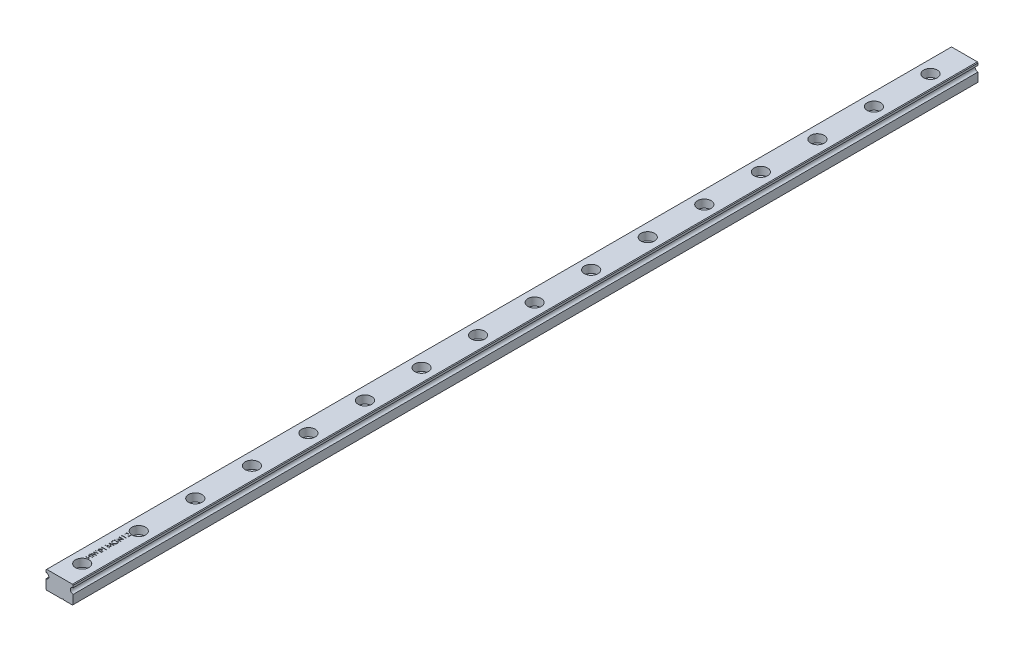
SolidWorks part; units mm, degrees
material "镀铬不锈钢"
ref_plane "前视基准面" through (0, 0, 0) normal (0, 0, 1) x (1, 0, 0)
ref_plane "上视基准面" through (0, 0, 0) normal (0, 1, 0) x (1, 0, 0)
ref_plane "右视基准面" through (0, 0, 0) normal (1, 0, 0) x (0, 0, -1)
sketch "草图1" plane through (0, 0, 0) normal (0, 0, 1) x (1, 0, 0)
  line L2 (-5.7, 0) -> (1.2, 0)
  line L3 (6, 0.3) -> (6, 4.25)
  line L4 (5.7, 0) -> (6, 0.3)
  line L5 (5.7, 8) -> (-5.7, 8)
  line L6 (-6, 0.3) -> (-5.7, 0)
  line L7 (6, 7.7) -> (5.7, 8)
  line L8 (-6, 7.7) -> (-6, 6.75)
  line L9 (-6, 4.25) -> (-6, 0.3)
  line L10 (0, 8) -> (0, 0) construction
  line L11 (-5.7, 8) -> (-6, 7.7)
  line L12 (1.8, 0) -> (5.7, 0)
  line L13 (6, 6.75) -> (6, 7.7)
  arc A0 (-6, 4.25) -> (-6, 6.75) centre (-6, 5.5) ccw
  arc A1 (1.8, 0) -> (1.2, 0) centre (1.5, 0) ccw
  arc A2 (6, 6.75) -> (6, 4.25) centre (6, 5.5) ccw
extrude "凸台-拉伸1" add sketch "草图1" against normal blind 400
hole_wizard "M3 六角凹头螺钉的柱形沉头孔1" positions "草图3" profile "草图2" counterbore size "M3" standard "ISO" end condition through all
sketch "草图3" plane through (1.75, 8, 16.5167) normal (0, 1, 0) x (-1, 0, 0)
  point P0 (1.75, -26.5167)
  dimension "D1" = 10
sketch "草图2" plane through (0, 8, -10) normal (1, 0, 0) x (0, 0, 1)
  line L0 (0, 0) -> (0, 8)
  line L1 (0, 8) -> (1.75, 8)
  line L3 (1.75, 8) -> (1.75, 3.5)
  line L4 (1.75, 3.5) -> (3, 3.5)
  line L5 (3, 3.5) -> (3, 0)
  line L7 (3, 0) -> (0, 0)
  line L11 (0, -6.35) -> (0, 107.95) construction
  dimension "通孔孔直径" = 3.5
  dimension "通孔孔深度" = 8
  dimension "柱形沉头孔直径" = 6
  dimension "柱形沉头孔深度" = 3.5
pattern_linear "阵列(线性)1" count 16 spacing 25 along (0, 0, -1) of "M3 六角凹头螺钉的柱形沉头孔1"
sketch "草图6" plane through (0, 8, 0) normal (0, 1, 0) x (1, 0, 0)
  line L0 (0, 10) -> (0, 35) construction
  text T0 "HIWIN MGN12" font "Century Gothic" height 2
extrude "切除-拉伸1" cut sketch "草图6" against normal blind 0.1
equation "\"D1@凸台-拉伸1\"=400"
